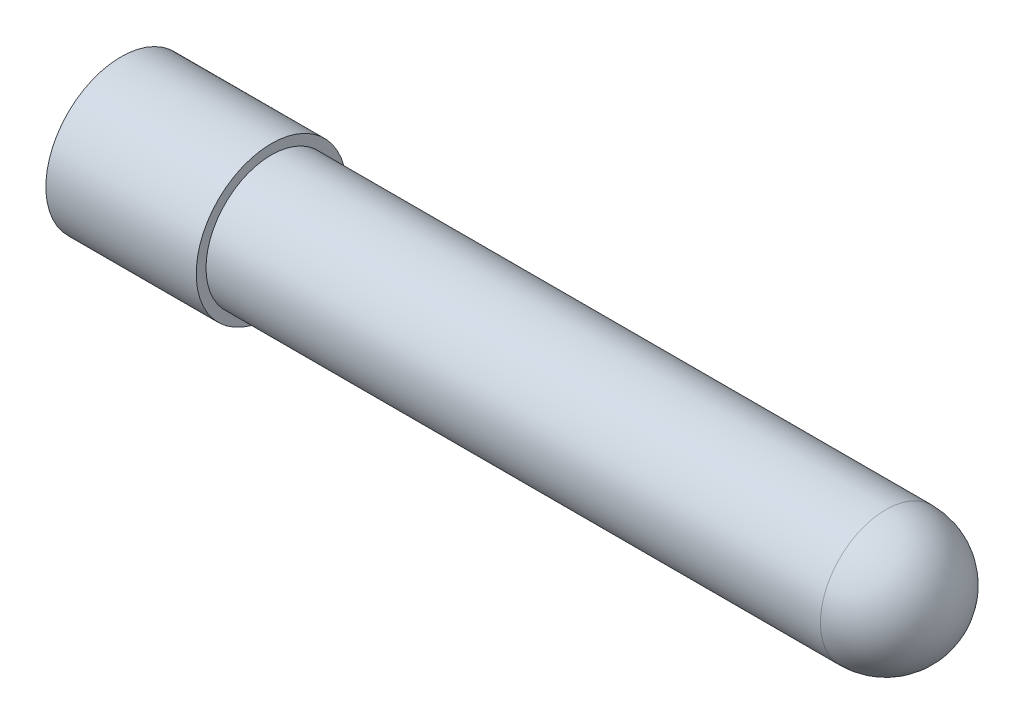
SolidWorks part; units mm, degrees
ref_plane "前视基准面" through (0, 0, 0) normal (0, 0, 1) x (1, 0, 0)
ref_plane "上视基准面" through (0, 0, 0) normal (0, 1, 0) x (1, 0, 0)
ref_plane "右视基准面" through (0, 0, 0) normal (1, 0, 0) x (0, 0, -1)
sketch "草图1" plane through (0, 0, 0) normal (1, 0, 0) x (0, 0, -1)
  circle A0 centre (0, 0) radius 5.75
  dimension "D1" = 11.5
extrude "凸台-拉伸1" add sketch "草图1" along normal blind 11.5
sketch "草图3" plane through (0, 0, 0) normal (-1, 0, 0) x (0, 0, 1)
  circle A0 centre (0, 0) radius 5
  dimension "D1" = 10
extrude "凸台-拉伸2" add sketch "草图3" against normal blind 63.5
fillet "圆角1" radius 5 1 edges at (63.5, 0, 5)
sketch "草图4" plane through (0, 0, 0) normal (-1, 0, 0) x (0, 0, 1)
  circle A0 centre (0, 0) radius 3
  dimension "D1" = 6
extrude "切除-拉伸1" cut sketch "草图4" against normal blind 4
